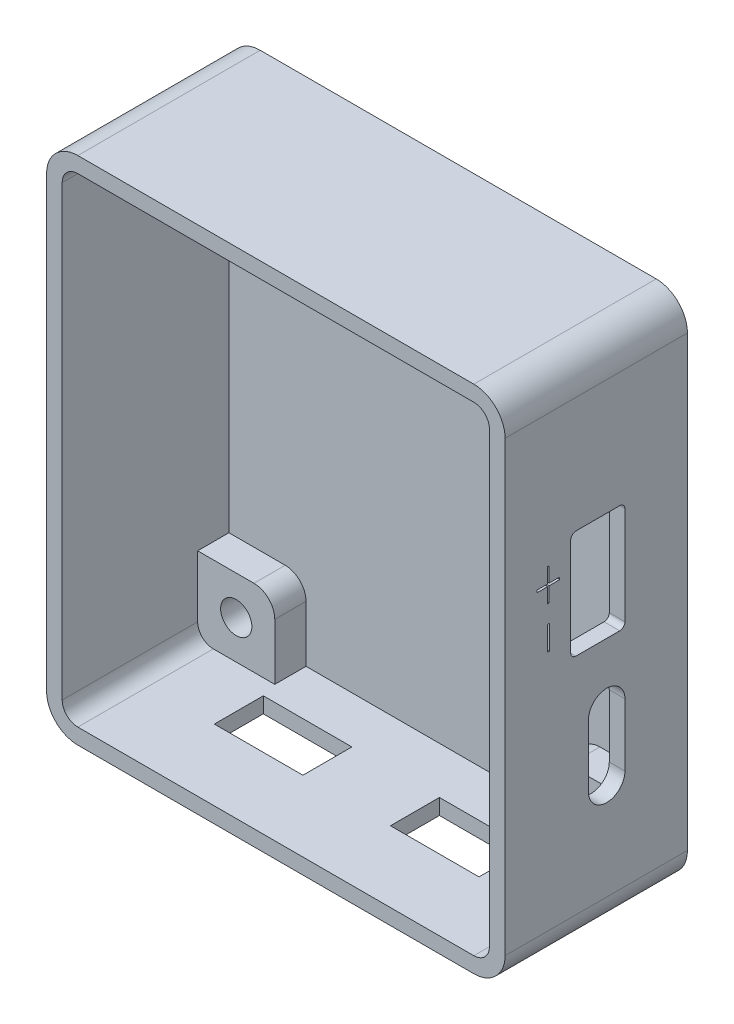
SolidWorks part; units mm, degrees
ref_plane "前视基准面" through (0, 0, 0) normal (0, 0, 1) x (1, 0, 0)
ref_plane "上视基准面" through (0, 0, 0) normal (0, 1, 0) x (1, 0, 0)
ref_plane "右视基准面" through (0, 0, 0) normal (1, 0, 0) x (0, 0, -1)
other "Configuration Table"
sketch "草图1" plane through (0, 0, 0) normal (0, 0, 1) x (1, 0, 0)
  line L1 (-19, -24.5) -> (19, -24.5)
  line L2 (-22, -21.5) -> (-22, 21.5)
  line L3 (-19, 24.5) -> (19, 24.5)
  line L4 (22, -21.5) -> (22, 21.5)
  line L5 (-22, -24.5) -> (22, 24.5) construction
  line L6 (-22, 24.5) -> (22, -24.5) construction
  arc A0 (19, -24.5) -> (22, -21.5) centre (19, -21.5) ccw
  arc A1 (-19, -24.5) -> (-22, -21.5) centre (-19, -21.5) cw
  arc A2 (19, 24.5) -> (22, 21.5) centre (19, 21.5) cw
  arc A3 (-22, 21.5) -> (-19, 24.5) centre (-19, 21.5) cw
  point P0 (0, 0)
  dimension "D3" = 3
  dimension "D1" = 49
  dimension "D2" = 44
extrude "凸台-拉伸1" add sketch "草图1" along normal blind 1.5
sketch "草图4" plane through (0, 0, 1.5) normal (0, 0, 1) x (1, 0, 0)
  line L0 (-19, -24.5) -> (19, -24.5) construction
  line L1 (-22, 21.5) -> (-22, -21.5) construction
  line L2 (22, -21.5) -> (22, 21.5) construction
  line L3 (19, 24.5) -> (-19, 24.5) construction
  line L4 (-19, -24.5) -> (19, -24.5)
  line L5 (-22, 21.5) -> (-22, -21.5)
  line L6 (22, -21.5) -> (22, 21.5)
  line L7 (19, 24.5) -> (-19, 24.5)
  line L8 (20.5, -21.5) -> (20.5, 21.5)
  line L9 (19, 23) -> (-19, 23)
  line L10 (-20.5, 21.5) -> (-20.5, -21.5)
  line L11 (-19, -23) -> (19, -23)
  arc A0 (-22, -21.5) -> (-19, -24.5) centre (-19, -21.5) ccw construction
  arc A1 (-19, 24.5) -> (-22, 21.5) centre (-19, 21.5) ccw construction
  arc A2 (19, -24.5) -> (22, -21.5) centre (19, -21.5) ccw construction
  arc A3 (22, 21.5) -> (19, 24.5) centre (19, 21.5) ccw construction
  arc A4 (-22, -21.5) -> (-19, -24.5) centre (-19, -21.5) ccw
  arc A5 (-19, 24.5) -> (-22, 21.5) centre (-19, 21.5) ccw
  arc A6 (19, -24.5) -> (22, -21.5) centre (19, -21.5) ccw
  arc A7 (22, 21.5) -> (19, 24.5) centre (19, 21.5) ccw
  arc A8 (20.5, 21.5) -> (19, 23) centre (19, 21.5) ccw
  arc A9 (-19, 23) -> (-20.5, 21.5) centre (-19, 21.5) ccw
  arc A10 (-20.5, -21.5) -> (-19, -23) centre (-19, -21.5) ccw
  arc A11 (19, -23) -> (20.5, -21.5) centre (19, -21.5) ccw
  dimension "D1" = 1.5
extrude "凸台-拉伸2" add sketch "草图4" along normal blind 16
sketch "草图6" plane through (0, 0, 1.5) normal (0, 0, 1) x (1, 0, 0)
  line L0 (-13.1, 23) -> (-13.1, 17.6)
  line L1 (19, 23) -> (-19, 23) construction
  line L2 (-15.1, 15.6) -> (-20.5, 15.6)
  line L3 (-20.5, 21.5) -> (-20.5, -21.5) construction
  line L4 (0, 23) -> (0, -32.9365) construction
  line L5 (-20.5, 0) -> (27.6187, 0) construction
  line L6 (15.1, 15.6) -> (20.5, 15.6)
  line L7 (13.1, 23) -> (13.1, 17.6)
  line L8 (-15.1, -15.6) -> (-20.5, -15.6)
  line L9 (-13.1, -23) -> (-13.1, -17.6)
  line L10 (13.1, -23) -> (13.1, -17.6)
  line L11 (15.1, -15.6) -> (20.5, -15.6)
  line L12 (-19, -23) -> (19, -23) construction
  line L13 (20.5, -21.5) -> (20.5, 21.5) construction
  line L14 (-19, -23) -> (19, -23)
  line L15 (-20.5, 21.5) -> (-20.5, -21.5)
  line L16 (19, 23) -> (-19, 23)
  line L17 (20.5, -21.5) -> (20.5, 21.5)
  circle A0 centre (-16.8, 19.3) radius 1.5
  arc A1 (-13.1, 17.6) -> (-15.1, 15.6) centre (-15.1, 17.6) cw
  arc A3 (13.1, 17.6) -> (15.1, 15.6) centre (15.1, 17.6) ccw
  arc A5 (-13.1, -17.6) -> (-15.1, -15.6) centre (-15.1, -17.6) ccw
  arc A6 (13.1, -17.6) -> (15.1, -15.6) centre (15.1, -17.6) cw
  arc A8 (19, -23) -> (20.5, -21.5) centre (19, -21.5) ccw construction
  arc A9 (-20.5, -21.5) -> (-19, -23) centre (-19, -21.5) ccw construction
  arc A10 (-19, 23) -> (-20.5, 21.5) centre (-19, 21.5) ccw construction
  arc A11 (20.5, 21.5) -> (19, 23) centre (19, 21.5) ccw construction
  arc A12 (19, -23) -> (20.5, -21.5) centre (19, -21.5) ccw
  arc A13 (-20.5, -21.5) -> (-19, -23) centre (-19, -21.5) ccw
  arc A14 (-19, 23) -> (-20.5, 21.5) centre (-19, 21.5) ccw
  arc A15 (20.5, 21.5) -> (19, 23) centre (19, 21.5) ccw
  circle A16 centre (16.8, 19.3) radius 1.5
  circle A17 centre (16.8, -19.3) radius 1.5
  circle A18 centre (-16.8, -19.3) radius 1.5
  point P11 (-13.1, 15.6)
  dimension "D5" = 3
  dimension "D6" = 2
  dimension "D1" = 3.7
  dimension "D2" = 3.7
  dimension "D3" = 7.4
  dimension "D4" = 7.4
extrude "凸台-拉伸4" add sketch "草图6" along normal blind 3
sketch "草图7" plane through (22, 0, 0) normal (1, 0, 0) x (0, 0, -1)
  line L0 (-17.5, 21.5) -> (0, 21.5) construction
  line L1 (-10.7, 10.4) -> (-6.5, 10.4)
  line L2 (-11.2, 9.9) -> (-11.2, 0.5)
  line L3 (-10.7, 0) -> (-6.5, 0)
  line L4 (-6, 9.9) -> (-6, 0.5)
  line L5 (-4.5, 15.6) -> (-4.5, 21.5) construction
  line L6 (-7.75, -5.9) -> (-7.75, -11.9) construction
  line L7 (-6, -5.9) -> (-6, -11.9)
  line L8 (-9.5, -5.9) -> (-9.5, -11.9)
  line L9 (-17.5, -21.5) -> (0, -21.5) construction
  line L10 (-4.5, -21.5) -> (-4.5, -15.6) construction
  arc A0 (-11.2, 0.5) -> (-10.7, 0) centre (-10.7, 0.5) ccw
  arc A1 (-6.5, 0) -> (-6, 0.5) centre (-6.5, 0.5) ccw
  arc A2 (-6.5, 10.4) -> (-6, 9.9) centre (-6.5, 9.9) cw
  arc A3 (-10.7, 10.4) -> (-11.2, 9.9) centre (-10.7, 9.9) ccw
  arc A4 (-6, -5.9) -> (-9.5, -5.9) centre (-7.75, -5.9) ccw
  arc A5 (-9.5, -11.9) -> (-6, -11.9) centre (-7.75, -11.9) ccw
  point P10 (-11.2, 0)
  point P15 (-6, 10.4)
  point P18 (-11.2, 10.4)
  point P21 (-7.75, -8.9)
  dimension "D5" = 0.5
  dimension "D1" = 11.1
  dimension "D2" = 1.5
  dimension "D3" = 5.2
  dimension "D4" = 10.4
  dimension "D6" = 9.6
  dimension "D7" = 6
  dimension "D8" = 3.5
  dimension "D9" = 1.5
extrude "切除-拉伸1" cut sketch "草图7" against normal up to surface (1.5 mm away) up to face at (20.5, 0, 7)
sketch "草图9" plane through (0, -24.5, 0) normal (0, -1, 0) x (1, 0, 0)
  line L0 (-19, 4.5) -> (-13.1, 4.5) construction
  line L1 (-12.7, 10.7) -> (-4.2, 10.7)
  line L2 (-12.7, 10.7) -> (-12.7, 6)
  line L3 (-12.7, 6) -> (-4.2, 6)
  line L4 (-4.2, 10.7) -> (-4.2, 6)
  line L5 (4.2, 10.7) -> (12.7, 10.7)
  line L6 (4.2, 10.7) -> (4.2, 6)
  line L7 (4.2, 6) -> (12.7, 6)
  line L8 (12.7, 10.7) -> (12.7, 6)
  line L9 (13.1, 4.5) -> (19, 4.5) construction
  line L10 (19, 17.5) -> (19, 0) construction
  line L11 (-19, 17.5) -> (-19, 0) construction
  dimension "D1" = 1.5
  dimension "D2" = 1.5
  dimension "D3" = 8.5
  dimension "D4" = 6.3
  dimension "D5" = 6.3
  dimension "D6" = 8.5
  dimension "D7" = 4.7
  dimension "D8" = 4.7
extrude "切除-拉伸2" cut sketch "草图9" against normal up to surface (1.5 mm away) up to face at (0, -23, 7)
sketch "草图10" plane through (0, -24.5, 0) normal (0, -1, 0) x (1, 0, 0)
  text T0 "LHGV"
  text T1 "CTGV\r\n"
extrude "切除-拉伸3" cut sketch "草图10" against normal blind 0.4
sketch "草图11" plane through (22, 0, 0) normal (1, 0, 0) x (0, 0, -1)
  line L1 (-13.424, 3.9955) -> (-13.256, 3.9955)
  line L2 (-13.424, 3.9955) -> (-13.424, 1.6723)
  line L3 (-13.424, 1.6723) -> (-13.256, 1.6723)
  line L4 (-13.256, 3.9955) -> (-13.256, 1.6723)
  text T0 "＋"
extrude "切除-拉伸4" cut sketch "草图11" against normal blind 0.4
